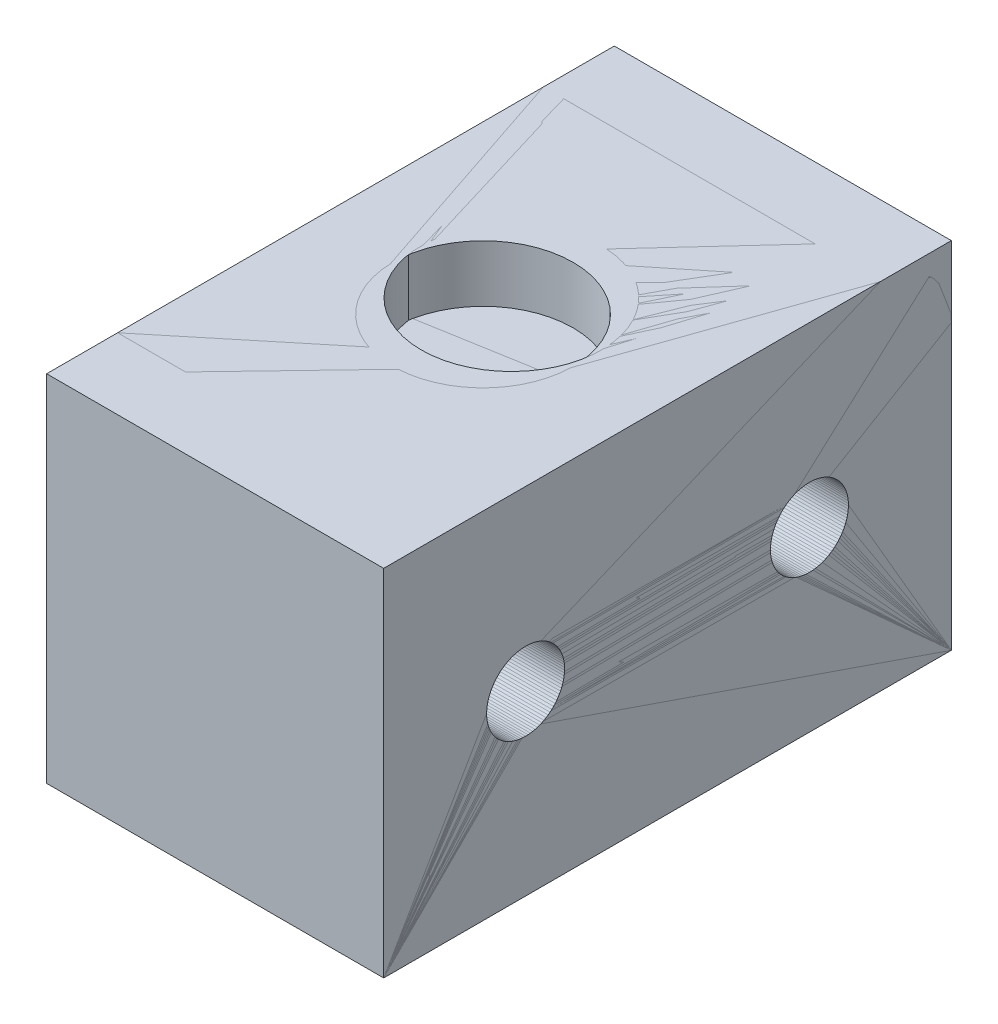
SolidWorks part; units mm, degrees
other "Symétrie_D"
ref_plane "Plan de face" through (0, 0, 0) normal (0, 0, 1) x (1, 0, 0)
ref_plane "Plan de dessus" through (0, 0, 0) normal (0, 1, 0) x (1, 0, 0)
ref_plane "Plan de droite" through (0, 0, 0) normal (1, 0, 0) x (0, 0, -1)
sketch "Esquisse2" plane through (0, 0, 0) normal (0, 0, 1) x (1, 0, 0)
  line L0 (-24, 95) -> (-24, -95) construction
  line L1 (0, 100) -> (-23.75, 100)
  line L2 (0, 100) -> (0, 75)
  line L3 (0, 75) -> (-23.75, 75)
  line L4 (-23.75, 100) -> (-23.75, 75)
  line L5 (0, 95) -> (0, -95) construction
  line L6 (3.175, 100) -> (0, 100) construction
  dimension "D1" = 0.25
  dimension "D2" = 25
extrude "Boss.-Extru.1" add sketch "Esquisse2" against normal blind 40
sketch "Esquisse3" plane through (0, 100, 0) normal (0, 1, 0) x (1, 0, 0)
  line L0 (3.175, 21) -> (-27.175, 21) construction
  circle A0 centre (-12, 21) radius 6.35
  dimension "D1" = 12.7
extrude "Enlèv. mat.-Extru.1" cut sketch "Esquisse3" against normal blind 4
hole_wizard "Dégagement M51" positions "Esquisse3D1" profile "Esquisse5" hole size "M5" standard "Ansi Metric" end condition through all
sketch3d "Esquisse3D1"
  line L0 (0, 75, 0) -> (0, 100, 0) construction
  point P0 (0, 87.5, -10)
  point P2 (0, 87.5, -30)
  point P8 (0, 87.5, 0)
  dimension "D1" = 20
  dimension "D2" = 10
sketch "Esquisse5" plane through (0, 87.5, -10) normal (0, 1, 0) x (0, 0, -1)
  line L0 (0, 0) -> (0, 23.75)
  line L1 (0, 23.75) -> (2.75, 23.75)
  line L2 (2.75, 23.75) -> (2.75, 0)
  line L5 (2.75, 0) -> (0, 0)
  line L11 (0, -6.35) -> (0, 107.95) construction
  dimension "Diamètre du perçage jusqu'au prochain" = 5.5
  dimension "Profondeur du perçage jusqu'au prochain" = 23.75
ref_plane "Plan1" through (0, 0, -20) normal (0, 0, 1) x (1, 0, 0)
fillet "Congé1" radius 5 1 edges at (-11.875, 100, 0)
mirror "Symétrie1" about plane through (0, 0, -20) normal (0, 0, 1) of bodies 103
